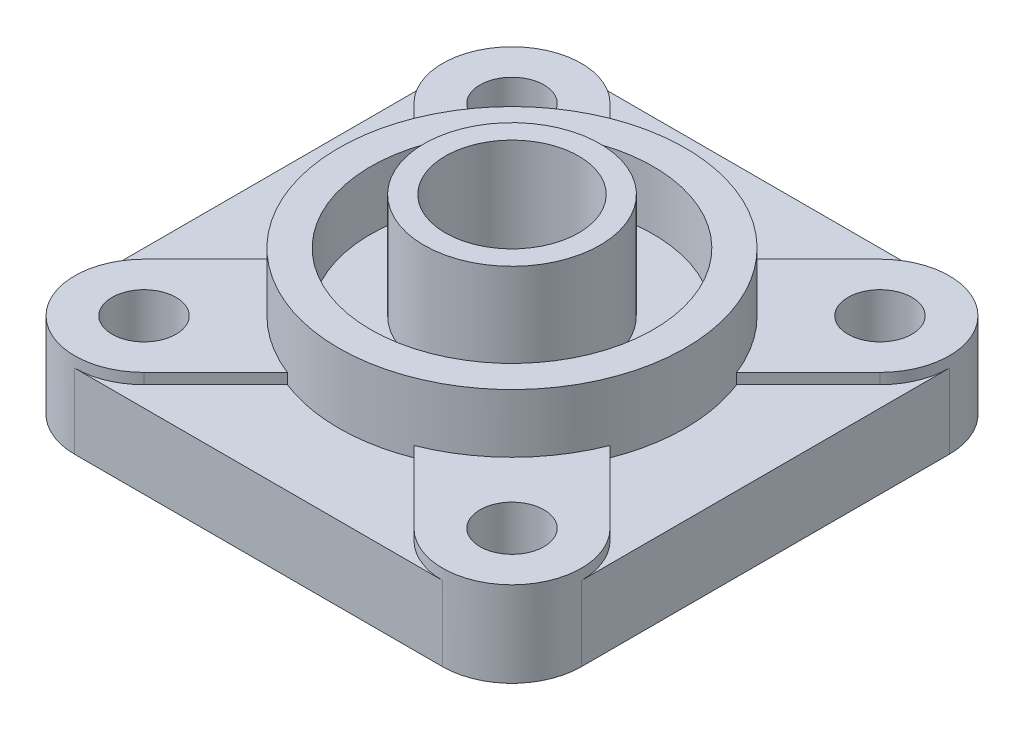
SolidWorks part; units mm, degrees
ref_plane "Front Plane" through (0, 0, 0) normal (0, 0, 1) x (1, 0, 0)
ref_plane "Top Plane" through (0, 0, 0) normal (0, 1, 0) x (1, 0, 0)
ref_plane "Right Plane" through (0, 0, 0) normal (1, 0, 0) x (0, 0, -1)
sketch "Sketch1" plane through (0, 0, 0) normal (0, 1, 0) x (1, 0, 0)
  line L1 (-47.5, -47.5) -> (47.5, -47.5)
  line L2 (-47.5, -47.5) -> (-47.5, 47.5)
  line L3 (-47.5, 47.5) -> (47.5, 47.5)
  line L4 (47.5, -47.5) -> (47.5, 47.5)
  line L5 (-47.5, -47.5) -> (47.5, 47.5) construction
  line L6 (-47.5, 47.5) -> (47.5, -47.5) construction
  point P0 (0, 0)
  dimension "D1" = 95
extrude "Boss-Extrude1" add sketch "Sketch1" along normal blind 14
sketch "Sketch2" plane through (0, 0, 0) normal (0, 1, 0) x (1, 0, 0)
  line L0 (-30.2548, 11.87) -> (-43.6924, 25.3076)
  line L1 (0, 0) -> (-47.5, 47.5) construction
  line L2 (-11.87, 30.2548) -> (-25.3076, 43.6924)
  line L3 (-47.5, 47.5) -> (-47.5, -47.5) construction
  line L4 (11.87, 30.2548) -> (25.3076, 43.6924)
  line L5 (30.2548, 11.87) -> (43.6924, 25.3076)
  line L6 (0, 0) -> (47.5, 47.5) construction
  line L7 (30.2548, -11.87) -> (43.6924, -25.3076)
  line L8 (11.87, -30.2548) -> (25.3076, -43.6924)
  line L9 (0, 0) -> (47.5, -47.5) construction
  line L10 (-11.87, -30.2548) -> (-25.3076, -43.6924)
  line L11 (-30.2548, -11.87) -> (-43.6924, -25.3076)
  line L12 (0, 0) -> (-47.5, -47.5) construction
  arc A0 (-11.87, 30.2548) -> (-30.2548, 11.87) centre (0, 0) ccw
  arc A1 (-43.6924, 25.3076) -> (-25.3076, 43.6924) centre (-34.5, 34.5) cw
  arc A2 (30.2548, 11.87) -> (11.87, 30.2548) centre (0, 0) ccw
  arc A3 (25.3076, 43.6924) -> (43.6924, 25.3076) centre (34.5, 34.5) cw
  arc A4 (11.87, -30.2548) -> (30.2548, -11.87) centre (0, 0) ccw
  arc A5 (43.6924, -25.3076) -> (25.3076, -43.6924) centre (34.5, -34.5) cw
  arc A6 (-30.2548, -11.87) -> (-11.87, -30.2548) centre (0, 0) ccw
  arc A7 (-25.3076, -43.6924) -> (-43.6924, -25.3076) centre (-34.5, -34.5) cw
  point P32 (0, 0)
  dimension "D1" = 65
  dimension "D2" = 26
  dimension "D3" = 4
extrude "Boss-Extrude2" add sketch "Sketch2" along normal blind 16
sketch "Sketch4" plane through (0, 14, 0) normal (0, 1, 0) x (1, 0, 0)
  circle A0 centre (0, 0) radius 32.5
  dimension "D1" = 65
extrude "Boss-Extrude3" add sketch "Sketch4" along normal blind 13
sketch "Sketch5" plane through (0, 27, 0) normal (0, 1, 0) x (1, 0, 0)
  circle A0 centre (0, 0) radius 12.5
  dimension "D1" = 25
extrude "Cut-Extrude1" cut sketch "Sketch5" against normal through all
sketch "Sketch6" plane through (0, 27, 0) normal (0, 1, 0) x (1, 0, 0)
  circle A0 centre (0, 0) radius 12.5 construction
  circle A1 centre (0, 0) radius 12.5 construction
  circle A2 centre (0, 0) radius 26.5
  circle A4 centre (0, 0) radius 32.5 construction
  circle A5 centre (0, 0) radius 16.5
  dimension "D1" = 6
  dimension "D2" = 4
extrude "Cut-Extrude2" cut sketch "Sketch6" against normal up to surface (11 mm away) up to face at (-30.5589, 16, -30.5589)
sketch "Sketch7" plane through (0, 0, 0) normal (0, 1, 0) x (1, 0, 0)
  circle A0 centre (0, 0) radius 12.5 construction
  circle A1 centre (0, 0) radius 16.5
  circle A2 centre (0, 0) radius 16.5
  circle A3 centre (0, 0) radius 12.5
  dimension "D1" = 0
extrude "Boss-Extrude4" add sketch "Sketch7" along normal blind 35.7
sketch "Sketch8" plane through (0, 0, 0) normal (0, 1, 0) x (1, 0, 0)
  line L0 (-47.5, -34.5) -> (-47.5, -47.5)
  line L1 (-34.5, 47.5) -> (-47.5, 47.5)
  line L2 (47.5, 34.5) -> (47.5, 47.5)
  line L3 (34.5, -47.5) -> (47.5, -47.5)
  line L4 (-47.5, -47.5) -> (47.5, -47.5)
  line L5 (47.5, -47.5) -> (47.5, 47.5)
  line L6 (47.5, 47.5) -> (-47.5, 47.5)
  line L7 (-47.5, 47.5) -> (-47.5, -47.5)
  line L8 (-47.5, -47.5) -> (-34.5, -47.5)
  line L9 (47.5, -47.5) -> (47.5, -34.5)
  line L10 (47.5, 47.5) -> (34.5, 47.5)
  line L11 (-47.5, 47.5) -> (-47.5, 34.5)
  arc A0 (-43.6924, -25.3076) -> (-25.3076, -43.6924) centre (-34.5, -34.5) ccw construction
  arc A1 (25.3076, -43.6924) -> (43.6924, -25.3076) centre (34.5, -34.5) ccw construction
  arc A2 (43.6924, 25.3076) -> (25.3076, 43.6924) centre (34.5, 34.5) ccw construction
  arc A3 (-25.3076, 43.6924) -> (-43.6924, 25.3076) centre (-34.5, 34.5) ccw construction
  arc A4 (-47.5, -34.5) -> (-34.5, -47.5) centre (-34.5, -34.5) ccw
  arc A5 (34.5, -47.5) -> (47.5, -34.5) centre (34.5, -34.5) ccw
  arc A6 (47.5, 34.5) -> (34.5, 47.5) centre (34.5, 34.5) ccw
  arc A7 (-34.5, 47.5) -> (-47.5, 34.5) centre (-34.5, 34.5) ccw
  dimension "D1" = 0
extrude "Cut-Extrude3" cut sketch "Sketch8" along normal through all
sketch "Sketch9" plane through (0, 0, 0) normal (0, 1, 0) x (1, 0, 0)
  circle A0 centre (-34.5, 34.5) radius 6
  circle A1 centre (34.5, 34.5) radius 6
  circle A2 centre (34.5, -34.5) radius 6
  circle A3 centre (-34.5, -34.5) radius 6
  point P3 (-58.0033, -23.1825)
  point P4 (0, 0)
  point P12 (0, 0)
  dimension "D1" = 12
  dimension "D2" = 4
extrude "Cut-Extrude5" cut sketch "Sketch9" along normal through all
